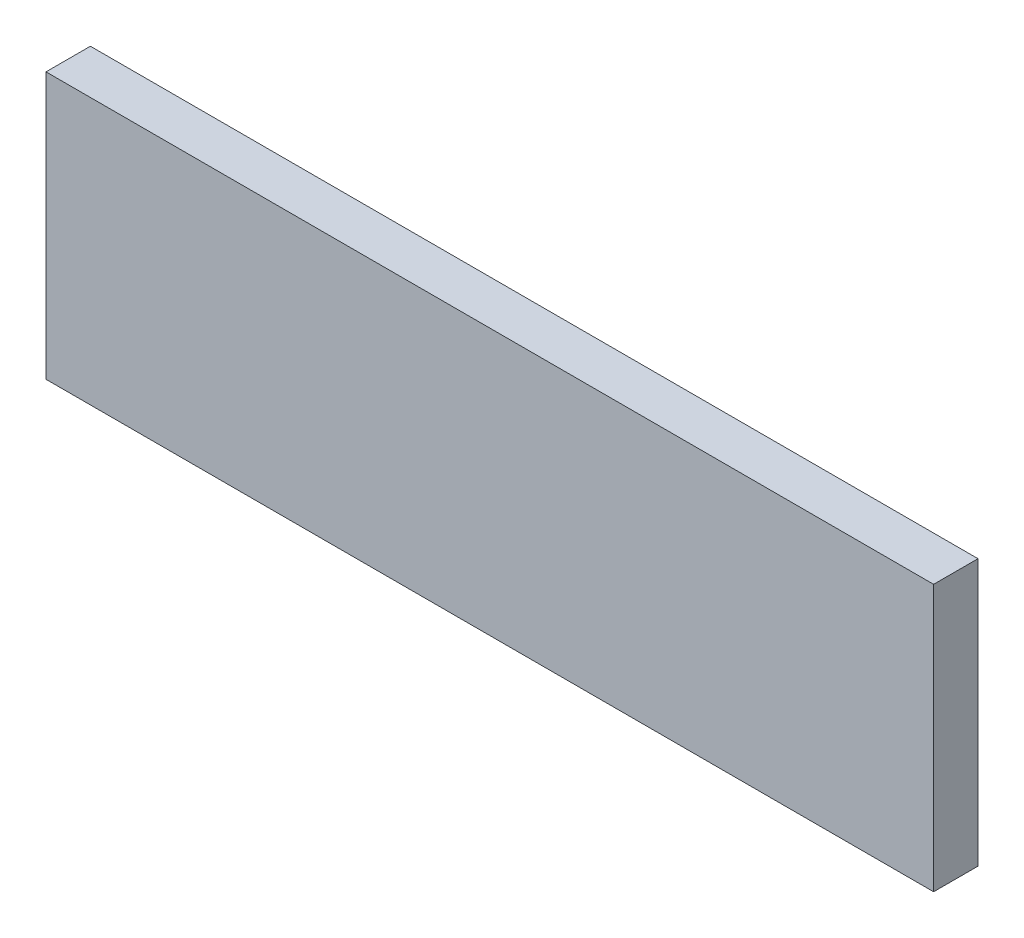
SolidWorks part; units mm, degrees
ref_plane "Front Plane" through (0, 0, 0) normal (0, 0, 1) x (1, 0, 0)
ref_plane "Top Plane" through (0, 0, 0) normal (0, 1, 0) x (1, 0, 0)
ref_plane "Right Plane" through (0, 0, 0) normal (1, 0, 0) x (0, 0, -1)
sketch "Sketch1" plane through (0, 0, 0) normal (0, 1, 0) x (1, 0, 0)
  line L0 (80.0432, 72.4539) -> (80.0432, -9.5461) construction
  line L1 (-59.9568, 5.4539) -> (40.0432, 5.4539)
  line L2 (-59.9568, 5.4539) -> (-59.9568, 0.4539)
  line L3 (-59.9568, 0.4539) -> (40.0432, 0.4539)
  line L4 (40.0432, 5.4539) -> (40.0432, 0.4539)
  line L5 (80.0432, -9.5461) -> (-69.9568, -9.5461) construction
  dimension "D1" = 100
  dimension "D2" = 5
  dimension "D3" = 40
  dimension "D4" = 10
extrude "Boss-Extrude1" add sketch "Sketch1" along normal blind 30
